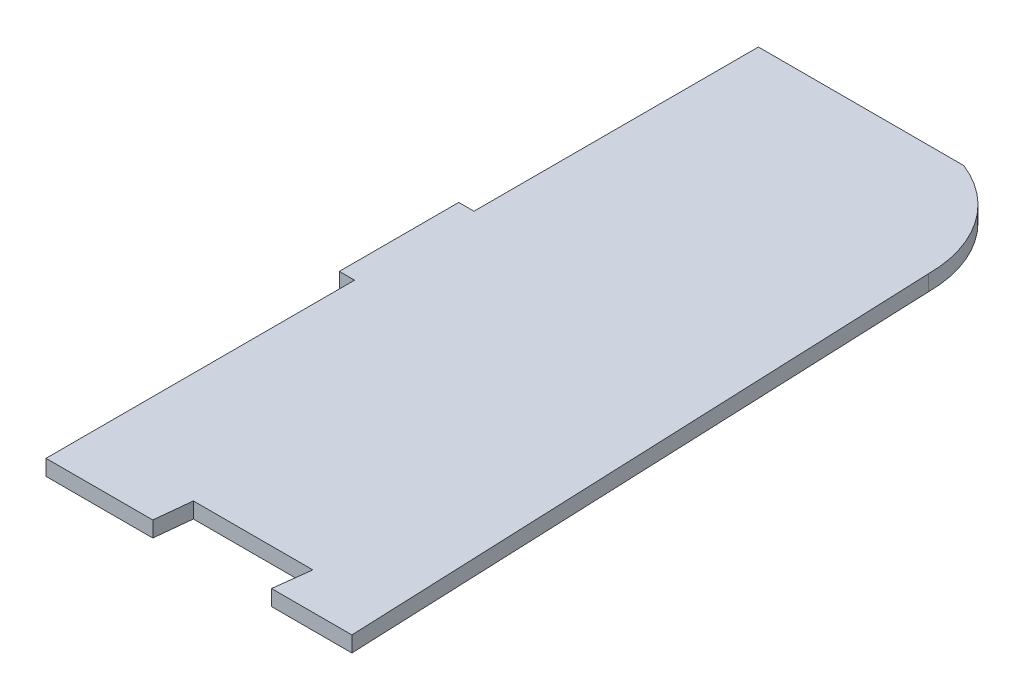
SolidWorks part; units mm, degrees
ref_plane "Front Plane" through (0, 0, 0) normal (0, 0, 1) x (1, 0, 0)
ref_plane "Top Plane" through (0, 0, 0) normal (0, 1, 0) x (1, 0, 0)
ref_plane "Right Plane" through (0, 0, 0) normal (1, 0, 0) x (0, 0, -1)
sketch "Sketch1" plane through (0, 0, 0) normal (0, 0, 1) x (1, 0, 0)
  line L1 (358.1218, 754.38) -> (137.9613, 754.38)
  line L2 (358.1218, 754.38) -> (562.8036, 754.38)
  line L3 (562.8036, 754.38) -> (562.8036, 744.38)
  line L4 (562.8036, 744.38) -> (137.9613, 744.38)
  line L5 (137.9613, 744.38) -> (137.9613, 754.38)
  dimension "D1" = 10
extrude "Boss-Extrude1" add sketch "Sketch1" along normal up to surface (454.5101 mm away)
sketch "Sketch3" plane through (0, 744.38, 0) normal (0, -1, 0) x (1, 0, 0)
  line L0 (255.63, 0) -> (255.63, 454.5101)
  line L1 (137.9613, 0) -> (562.8036, 0) construction
  line L2 (137.9613, 454.5101) -> (562.8036, 454.5101) construction
  line L3 (255.63, 454.5101) -> (137.9613, 454.5101)
  line L4 (137.9613, 454.5101) -> (137.9613, 0)
  line L5 (137.9613, 0) -> (255.63, 0)
extrude "Cut-Extrude1" cut sketch "Sketch3" against normal blind 10
sketch "Sketch4" plane through (0, 754.38, 0) normal (0, 1, 0) x (1, 0, 0)
  line L0 (265.3552, -454.5101) -> (265.3552, -257.6601)
  line L1 (562.8036, -454.5101) -> (255.63, -454.5101) construction
  line L2 (562.8036, 0) -> (255.63, 0) construction
  line L3 (265.3552, -454.5101) -> (255.63, -454.5101)
  line L4 (255.63, -454.5101) -> (255.63, -257.6601)
  line L5 (219.035, -257.6601) -> (265.3552, -257.6601) construction
  line L6 (219.035, -181.4601) -> (265.3552, -181.4601) construction
  line L7 (265.3552, -454.5101) -> (255.63, -454.5101)
  line L8 (265.3552, -257.6601) -> (255.63, -257.6601)
  line L9 (265.3552, -181.4601) -> (255.63, -181.4601)
  line L10 (255.63, -181.4601) -> (255.63, 0)
  line L11 (265.3552, -181.4601) -> (265.3552, 0)
  line L12 (333.4642, -454.5101) -> (369.7619, -561.8393)
  line L13 (333.4642, -454.5101) -> (335.9272, -431.0401)
  line L14 (335.9272, -431.0401) -> (412.1272, -431.0401)
  line L15 (412.1272, -431.0401) -> (409.2168, -454.5101)
  line L16 (409.2168, -454.5101) -> (460.5019, -454.5101)
  line L17 (460.5019, -454.5101) -> (444.8638, -70.9701)
  line L18 (369.7619, -561.8393) -> (604.2472, -525.6685)
  line L19 (604.2472, -525.6685) -> (681.4814, 161.1092)
  line L20 (681.4814, 161.1092) -> (358.7401, 101.8465)
  line L21 (358.7401, 101.8465) -> (368.6638, 5.2299)
  line L23 (265.3552, 0) -> (255.63, 0)
  line L24 (255.63, -181.4601) -> (255.63, 0)
  arc A1 (444.8638, -70.9701) -> (368.6638, 5.2299) centre (368.6638, -70.9701) ccw construction
  arc A2 (444.8638, -70.9701) -> (368.6638, 5.2299) centre (368.6638, -70.9701) ccw
  line M2 (562.8036, 0) -> (255.63, 0)
  line M3 (255.63, 0) -> (255.63, -454.5101)
  line M4 (255.63, -454.5101) -> (562.8036, -454.5101)
  line M5 (562.8036, -454.5101) -> (562.8036, 0)
extrude "Cut-Extrude3" cut sketch "Sketch4" against normal blind 63 contours L0 L8 M3 M4 | L9 L11 M2 M3 | L20 L21 L12 L18 L19 M2 M5 M4
